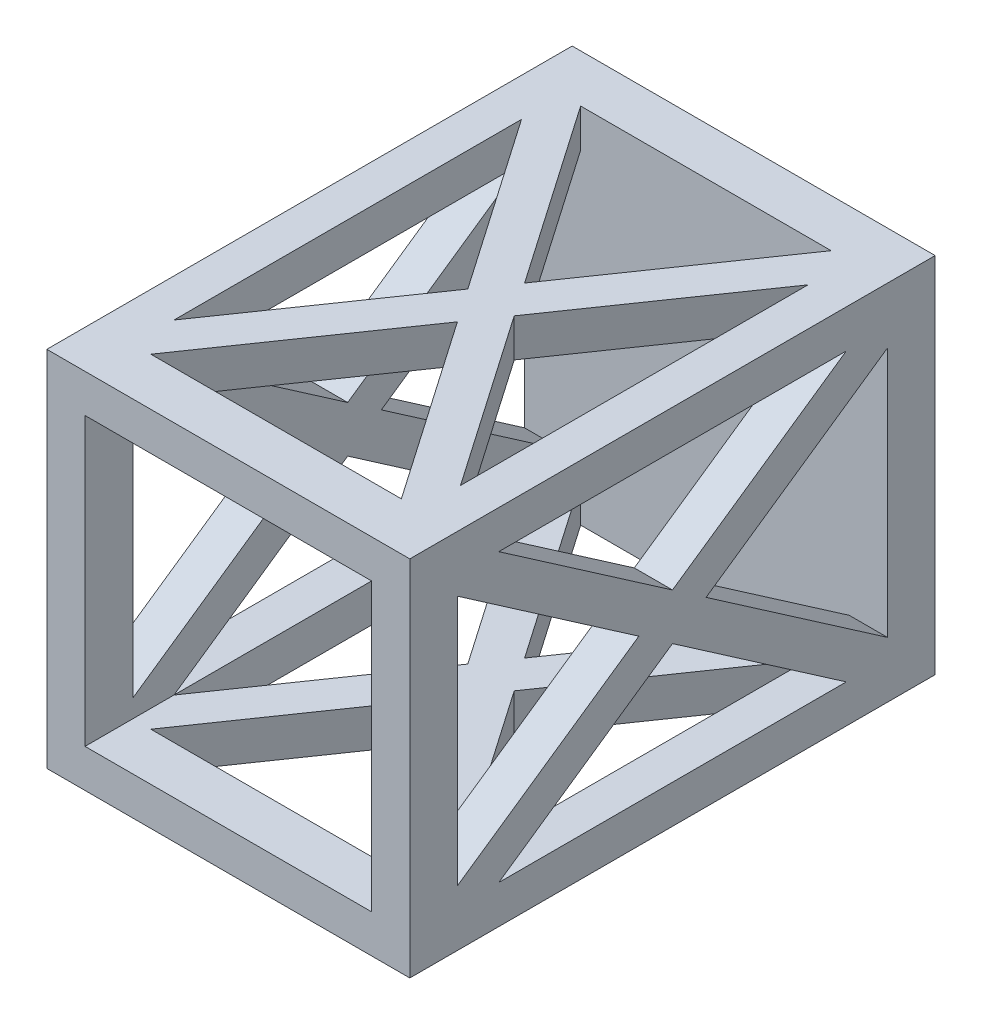
SolidWorks part; units mm, degrees
material "Plain Carbon Steel"
ref_plane "Front Plane" through (0, 0, 0) normal (0, 0, 1) x (1, 0, 0)
ref_plane "Top Plane" through (0, 0, 0) normal (0, 1, 0) x (1, 0, 0)
ref_plane "Right Plane" through (0, 0, 0) normal (1, 0, 0) x (0, 0, -1)
sketch "Sketch1" plane through (0, 0, 0) normal (0, 0, 1) x (1, 0, 0)
  line L6 (-38, -38) -> (38, -38)
  line L10 (-38, -38) -> (-38, 38)
  line L11 (-38, 38) -> (38, 38)
  line L12 (38, -38) -> (38, 38)
  line L13 (-38, -38) -> (38, 38) construction
  line L14 (-38, 38) -> (38, -38) construction
  point P0 (0, 0)
  dimension "D1" = 76
  dimension "D2" = 76
extrude "Boss-Extrude1" add sketch "Sketch1" along normal blind 110
sketch "Sketch2" plane through (0, 0, 110) normal (0, 0, 1) x (1, 0, 0)
  line L1 (-30, -30) -> (30, -30)
  line L2 (-30, -30) -> (-30, 30)
  line L3 (-30, 30) -> (30, 30)
  line L4 (30, -30) -> (30, 30)
  line L5 (-30, -30) -> (30, 30) construction
  line L6 (-30, 30) -> (30, -30) construction
  point P0 (0, 0)
  dimension "D1" = 60
  dimension "D2" = 60
extrude "Cut-Extrude1" cut sketch "Sketch2" against normal offset from surface (100 mm away) 10 up to face at (0, 0, 0)
sketch "Sketch4" plane through (0, 38, 0) normal (0, 1, 0) x (1, 0, 0)
  line L0 (-38, 0) -> (38, -110) construction
  line L1 (38, -110) -> (38, 0) construction
  line L2 (38, -110) -> (-38, -110) construction
  line L3 (38, 0) -> (-38, -110) construction
  line L4 (-38, -110) -> (-38, 0) construction
  line L5 (-26.229, -10) -> (0, -47.9631)
  line L6 (0, -47.9631) -> (26.229, -10)
  line L7 (26.229, -10) -> (-26.229, -10)
  line L8 (38, 0) -> (-38, 0) construction
  line L9 (0, 0) -> (0, -110) construction
  line L10 (38, -55) -> (-38, -55) construction
  line L11 (0, -62.0369) -> (26.229, -100)
  line L12 (-26.229, -100) -> (0, -62.0369)
  line L13 (26.229, -100) -> (-26.229, -100)
  line L14 (4.8619, -55) -> (30, -18.6159)
  line L15 (30, -18.6159) -> (30, -91.3841)
  line L16 (30, -91.3841) -> (4.8619, -55)
  line L17 (-30, -91.3841) -> (-4.8619, -55)
  line L18 (-30, -18.6159) -> (-30, -91.3841)
  line L19 (-4.8619, -55) -> (-30, -18.6159)
  point P27 (5.5071, -56.8956)
  point P30 (4.3935, -55)
  dimension "D1" = 4
  dimension "D2" = 4
  dimension "D3" = 10
  dimension "D4" = 4
  dimension "D5" = 4
  dimension "D6" = 8
extrude "Cut-Extrude2" cut sketch "Sketch4" against normal up to surface (76 mm away) up to face at (0, -38, 55)
sketch "Sketch5" plane through (-38, 0, 0) normal (-1, 0, 0) x (0, 0, 1)
  line L0 (110, 38) -> (0, -38) construction
  line L1 (0, 38) -> (110, -38) construction
  line L2 (55, 38) -> (55, -38) construction
  line L3 (110, 38) -> (0, 38) construction
  line L4 (110, -38) -> (0, -38) construction
  line L5 (110, 0) -> (0, 0) construction
  line L6 (110, 38) -> (110, -38) construction
  line L7 (18.6159, 30) -> (55, 4.8619)
  line L8 (55, 4.8619) -> (91.3841, 30)
  line L9 (91.3841, 30) -> (18.6159, 30)
  line L10 (91.3841, -30) -> (18.6159, -30)
  line L11 (55, -4.8619) -> (91.3841, -30)
  line L12 (18.6159, -30) -> (55, -4.8619)
  line L13 (10, 26.229) -> (47.9631, 0)
  line L14 (47.9631, 0) -> (10, -26.229)
  line L15 (10, -26.229) -> (10, 26.229)
  line L16 (0, 38) -> (0, -38) construction
  line L17 (62.0369, 0) -> (100, -26.229)
  line L18 (100, 26.229) -> (62.0369, 0)
  line L19 (100, -26.229) -> (100, 26.229)
  dimension "D1" = 4
  dimension "D2" = 4
  dimension "D3" = 8
  dimension "D4" = 4
  dimension "D5" = 4
  dimension "D6" = 10
extrude "Cut-Extrude3" cut sketch "Sketch5" against normal up to surface (76 mm away) up to face at (38, 0, 55)
